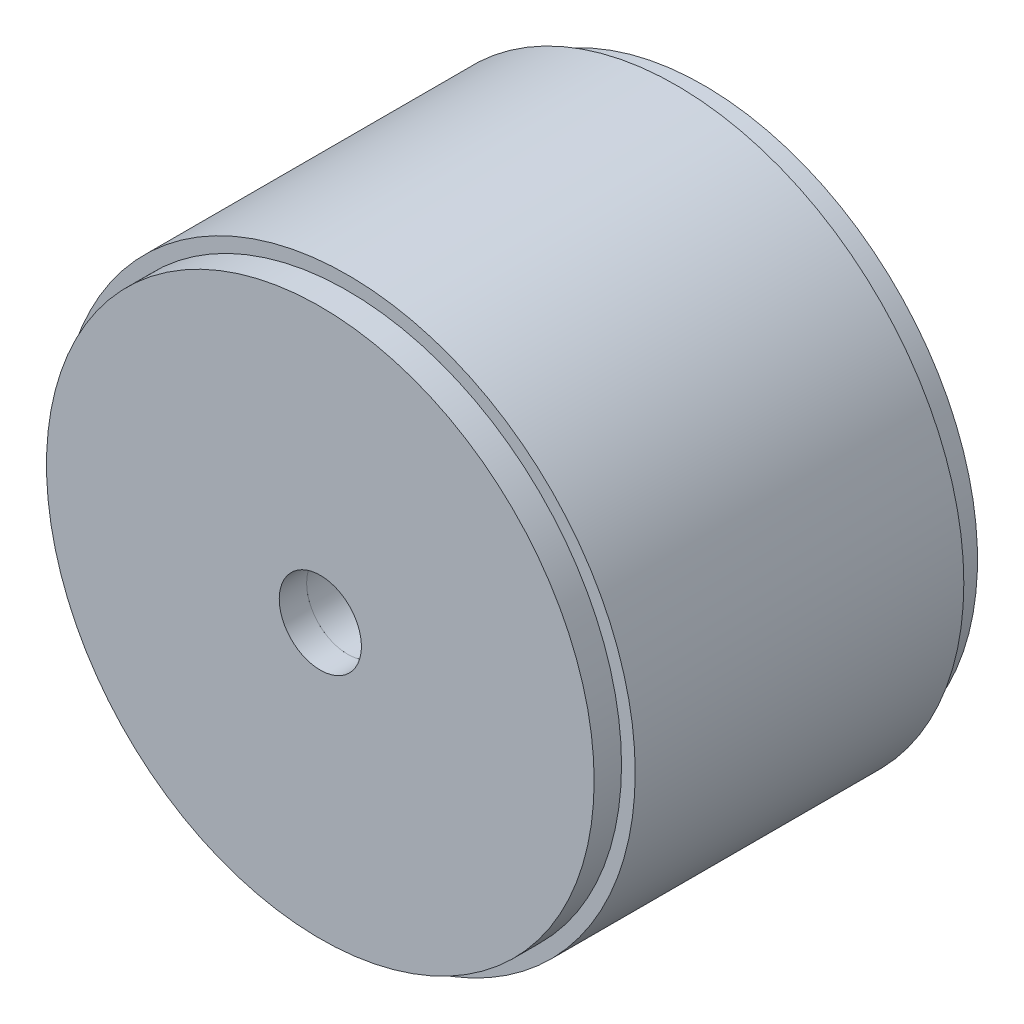
SolidWorks part; units mm, degrees
ref_plane "Front Plane" through (0, 0, 0) normal (0, 0, 1) x (1, 0, 0)
ref_plane "Top Plane" through (0, 0, 0) normal (0, 1, 0) x (1, 0, 0)
ref_plane "Right Plane" through (0, 0, 0) normal (1, 0, 0) x (0, 0, -1)
sketch "Croquis1" plane through (0, 0, 0) normal (0, 0, 1) x (1, 0, 0)
  circle A0 centre (0, 0) radius 10.5
  dimension "D1" = 21
extrude "Saliente-Extruir1" add sketch "Croquis1" along normal blind 12
sketch "Croquis2" plane through (0, 0, 12) normal (0, 0, 1) x (1, 0, 0)
  circle A0 centre (0, 0) radius 10
  dimension "D1" = 20
extrude "Saliente-Extruir2" add sketch "Croquis2" along normal blind 1 separate body
sketch "Croquis3" plane through (0, 0, 0) normal (0, 0, -1) x (-1, 0, 0)
  circle A0 centre (0, 0) radius 10
  dimension "D1" = 20
extrude "Saliente-Extruir3" add sketch "Croquis3" along normal blind 1 separate body
sketch "Croquis4" plane through (0, 0, -1) normal (0, 0, -1) x (-1, 0, 0)
  circle A0 centre (0, 0) radius 1.5
  dimension "D1" = 3
extrude "Cortar-Extruir1" cut sketch "Croquis4" against normal through all
